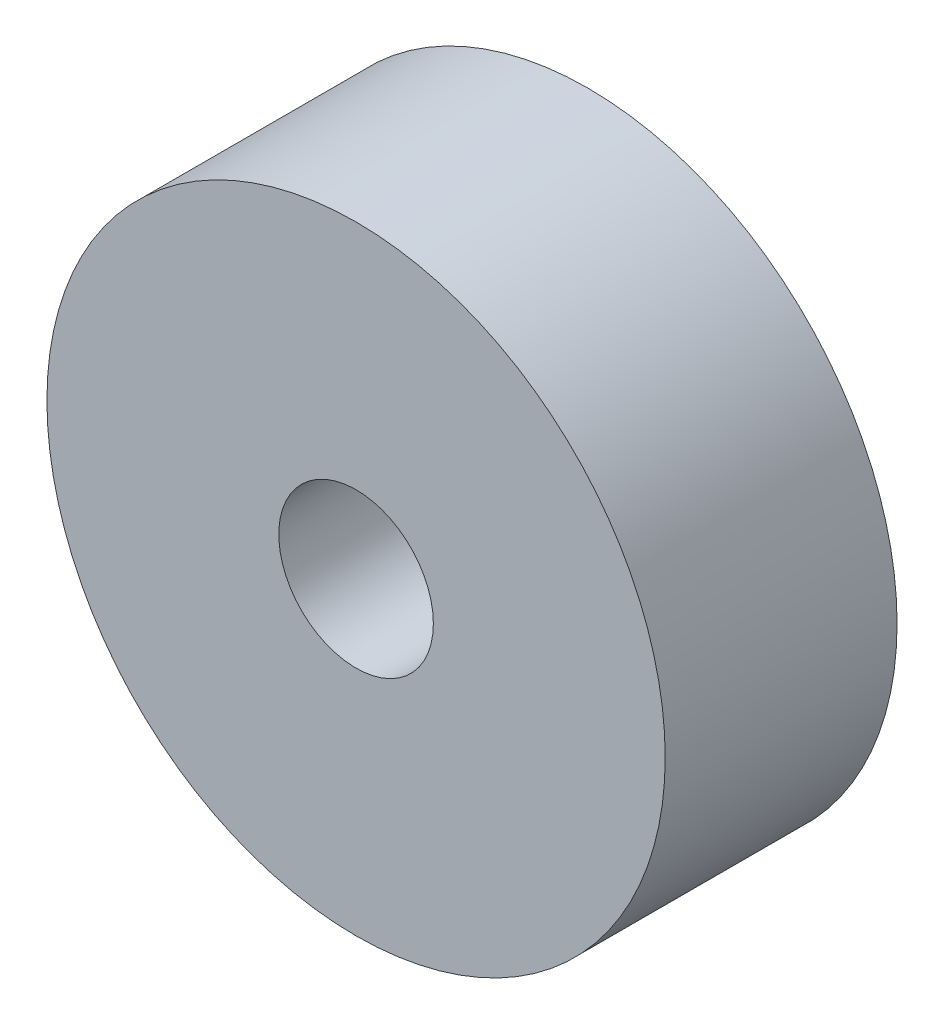
SolidWorks part; units mm, degrees
ref_plane "Front Plane" through (0, 0, 0) normal (0, 0, 1) x (1, 0, 0)
ref_plane "Top Plane" through (0, 0, 0) normal (0, 1, 0) x (1, 0, 0)
ref_plane "Right Plane" through (0, 0, 0) normal (1, 0, 0) x (0, 0, -1)
sketch "Sketch1" plane through (0, 0, 0) normal (0, 0, 1) x (1, 0, 0)
  circle A0 centre (0, 0) radius 4
  dimension "D1" = 8
extrude "Boss-Extrude1" add sketch "Sketch1" along normal blind 3
sketch "Sketch2" plane through (0, 0, 3) normal (0, 0, 1) x (1, 0, 0)
  circle A0 centre (0, 0) radius 1
  dimension "D1" = 2
extrude "Cut-Extrude1" cut sketch "Sketch2" against normal blind 3
